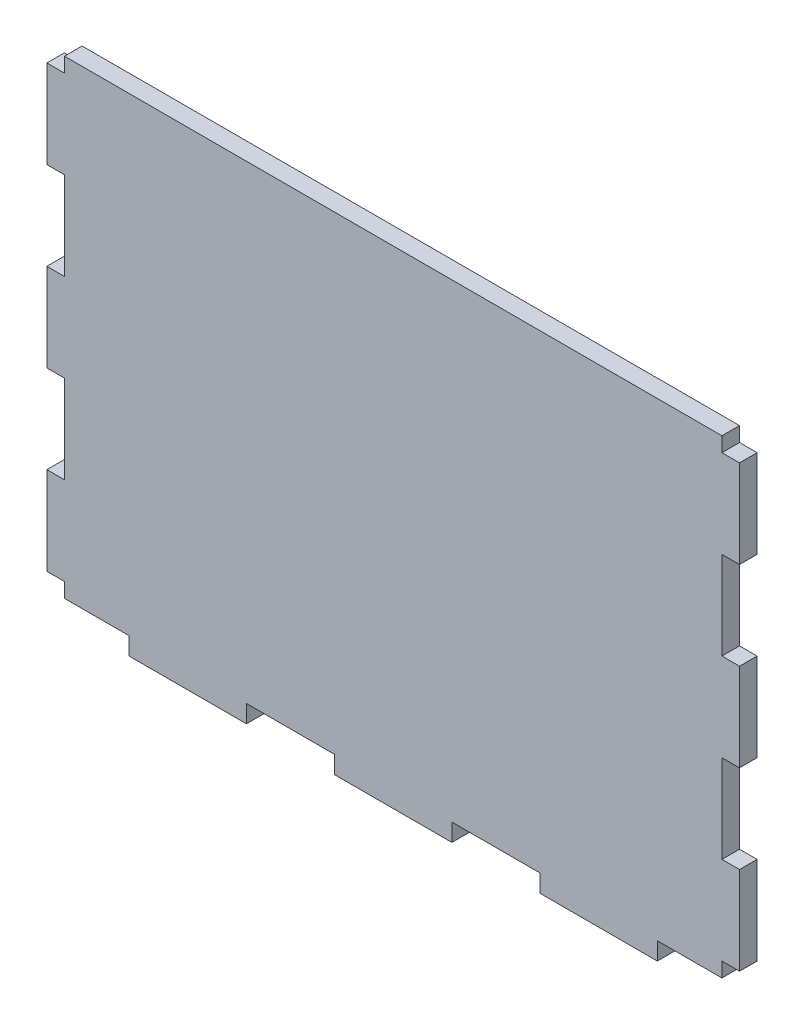
SolidWorks part; units mm, degrees
ref_plane "Front Plane" through (0, 0, 0) normal (0, 0, 1) x (1, 0, 0)
ref_plane "Top Plane" through (0, 0, 0) normal (0, 1, 0) x (1, 0, 0)
ref_plane "Right Plane" through (0, 0, 0) normal (1, 0, 0) x (0, 0, -1)
sketch "Sketch2" plane through (0, 0, 0) normal (0, 0, 1) x (1, 0, 0)
  line L0 (0, -55) -> (0, 55) construction
  line L1 (56, -40) -> (-56, -40)
  line L2 (56, -40) -> (56, 40)
  line L3 (56, 40) -> (-56, 40)
  line L4 (-56, -40) -> (-56, 40)
  line L5 (56, -40) -> (-56, 40) construction
  line L6 (56, 40) -> (-56, -40) construction
  line L7 (-10, -43) -> (10, -43)
  line L8 (-10, -43) -> (-10, -40)
  line L9 (-10, -40) -> (10, -40)
  line L10 (10, -43) -> (10, -40)
  line L11 (-10, -43) -> (10, -40) construction
  line L12 (-10, -40) -> (10, -43) construction
  line L13 (25, -43) -> (45, -43)
  line L14 (25, -43) -> (25, -40)
  line L15 (25, -40) -> (45, -40)
  line L16 (45, -43) -> (45, -40)
  line L17 (25, -43) -> (45, -40) construction
  line L18 (25, -40) -> (45, -43) construction
  line L19 (59, -7.5) -> (56, -7.5)
  line L20 (59, -7.5) -> (59, 7.5)
  line L21 (59, 7.5) -> (56, 7.5)
  line L22 (56, -7.5) -> (56, 7.5)
  line L23 (59, -7.5) -> (56, 7.5) construction
  line L24 (59, 7.5) -> (56, -7.5) construction
  line L25 (59, -37.5) -> (56, -37.5)
  line L26 (59, -37.5) -> (59, -22.5)
  line L27 (59, -22.5) -> (56, -22.5)
  line L28 (56, -37.5) -> (56, -22.5)
  line L29 (59, -37.5) -> (56, -22.5) construction
  line L30 (59, -22.5) -> (56, -37.5) construction
  line L31 (-59, 7.5) -> (-56, 7.5)
  line L32 (-56, -7.5) -> (-56, 7.5)
  line L33 (-59, -7.5) -> (-56, -7.5)
  line L34 (-59, -7.5) -> (-59, 7.5)
  line L35 (-59, -22.5) -> (-56, -22.5)
  line L36 (-56, -37.5) -> (-56, -22.5)
  line L37 (-59, -37.5) -> (-56, -37.5)
  line L38 (-59, -37.5) -> (-59, -22.5)
  line L39 (-25, -40) -> (-45, -40)
  line L40 (-45, -43) -> (-45, -40)
  line L41 (-25, -43) -> (-45, -43)
  line L42 (-25, -43) -> (-25, -40)
  line L43 (-10, -43) -> (-10, -40)
  line L44 (10, -43) -> (10, -40)
  line L45 (-59, 37.5) -> (-56, 37.5)
  line L46 (-56, -40) -> (56, -40)
  line L47 (-56, -40) -> (-56, -7.5)
  line L48 (-56, -7.5) -> (56, -7.5)
  line L49 (56, -40) -> (56, -7.5)
  line L50 (59, 22.5) -> (56, 22.5)
  line L51 (59, 22.5) -> (59, 37.5)
  line L52 (59, 37.5) -> (56, 37.5)
  line L53 (56, 22.5) -> (56, 37.5)
  line L54 (59, 22.5) -> (56, 37.5) construction
  line L55 (59, 37.5) -> (56, 22.5) construction
  line L56 (-56, 22.5) -> (-56, 37.5)
  line L57 (-59, 22.5) -> (-56, 22.5)
  line L58 (-59, 22.5) -> (-59, 37.5)
  point P0 (0, 0)
  point P6 (0, -41.5)
  point P11 (35, -41.5)
  point P16 (57.5, -30)
  point P17 (57.5, 0)
  point P40 (57.5, 30)
  point P45 (0, 0)
  dimension "D1" = 112
  dimension "D2" = 80
  dimension "D3" = 3
  dimension "D4" = 20
  dimension "D5" = 15
  dimension "D6" = 15
  dimension "D7" = 3
  dimension "D8" = 15
  dimension "D9" = 15
extrude "Boss-Extrude1" add sketch "Sketch2" along normal blind 3 contours L4 L1 L2 L3 | L41 L42 L1 L40 | L7 L10 L1 L8 | L13 L16 L1 L14 | L26 L27 L28 L25 | L35 L36 L37 L38 | L31 L32 L33 L34 | L20 L19 L22 L21 | L45 L56 L57 L58 | L51 L50 L53 L52
sketch "Sketch4" [suppressed] plane through (0, 0, 3) normal (0, 0, 1) x (1, 0, 0)
  line L0 (59, 7.5) -> (59, 22.5) construction
  line L1 (-59, 7.5) -> (59, 7.5)
  line L2 (-59, 7.5) -> (-59, 30)
  line L3 (-59, 30) -> (59, 30)
  line L4 (59, 7.5) -> (59, 30)
  line L5 (56, 30) -> (-56, 30) construction
  line L6 (0, -1.65) -> (0, 1.65) construction
  line L7 (-10, 4.5) -> (10, 4.5)
  line L8 (-10, 4.5) -> (-10, 7.5)
  line L9 (-10, 7.5) -> (10, 7.5)
  line L10 (10, 4.5) -> (10, 7.5)
  line L11 (-10, 4.5) -> (10, 7.5) construction
  line L12 (-10, 7.5) -> (10, 4.5) construction
  line L13 (-45, 4.5) -> (-25, 4.5)
  line L14 (-45, 4.5) -> (-45, 7.5)
  line L15 (-45, 7.5) -> (-25, 7.5)
  line L16 (-25, 4.5) -> (-25, 7.5)
  line L17 (-45, 4.5) -> (-25, 7.5) construction
  line L18 (-45, 7.5) -> (-25, 4.5) construction
  line L19 (45, 7.5) -> (25, 7.5)
  line L20 (25, 4.5) -> (25, 7.5)
  line L21 (45, 4.5) -> (25, 4.5)
  line L22 (45, 4.5) -> (45, 7.5)
  point P9 (0, 6)
  point P14 (-35, 6)
  line M15 (56, 7.5) -> (59, 7.5)
  line M16 (59, 7.5) -> (59, 22.5)
  line M17 (59, 22.5) -> (56, 22.5)
  line M18 (56, 22.5) -> (56, 30)
  line M19 (56, 30) -> (-56, 30)
  line M20 (-56, 30) -> (-56, 22.5)
  line M21 (-56, 22.5) -> (-59, 22.5)
  line M22 (-59, 22.5) -> (-59, 7.5)
  line M23 (-59, 7.5) -> (-56, 7.5)
  dimension "D1" = 3
  dimension "D2" = 20
  dimension "D3" = 15
extrude "Cut-Extrude2" [suppressed] cut sketch "Sketch4" against normal blind 10 contours L13 L16 L1 L14 | L7 L10 L1 L8 | L21 L22 L1 L20 | L1 M23 M15 M16 M17 M18 M19 M20 M21 M22
